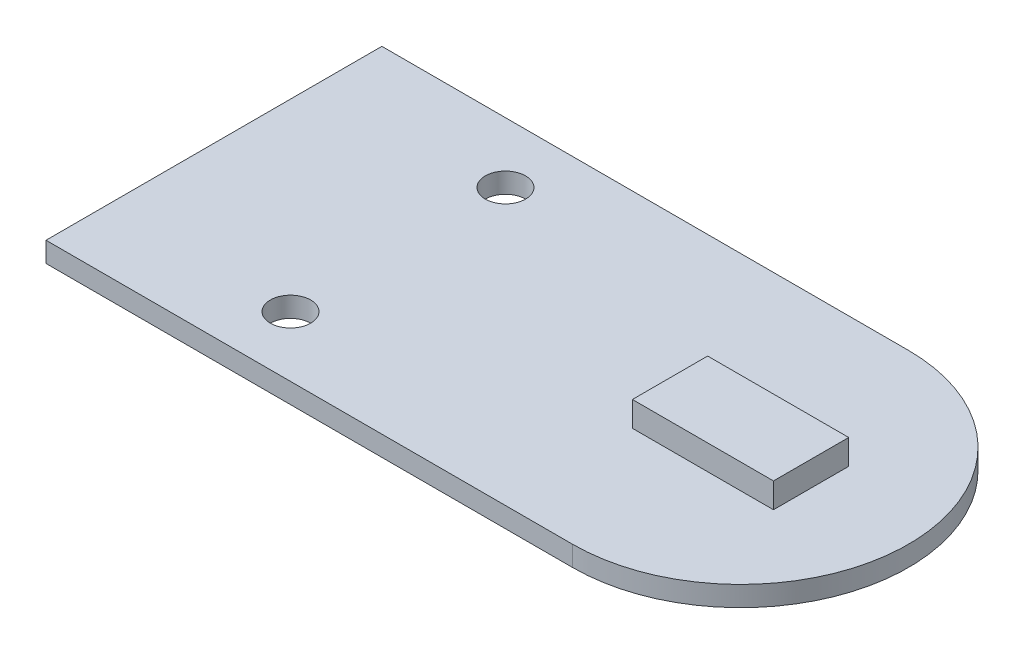
SolidWorks part; units mm, degrees
material "ABS"
ref_plane "Płaszczyzna przednia" through (0, 0, 0) normal (0, 0, 1) x (1, 0, 0)
ref_plane "Płaszczyzna górna" through (0, 0, 0) normal (0, 1, 0) x (1, 0, 0)
ref_plane "Płaszczyzna prawa" through (0, 0, 0) normal (1, 0, 0) x (0, 0, -1)
sketch "Szkic1" plane through (0, 0, 0) normal (0, 1, 0) x (1, 0, 0)
  line L0 (0, -55) -> (0, 55) construction
  line L1 (-39.2, 12.5) -> (0, 12.5)
  line L2 (-39.2, 12.5) -> (-39.2, -12.5)
  line L3 (-39.2, -12.5) -> (0, -12.5)
  line L5 (-55, 0) -> (55, 0) construction
  arc A0 (0, -12.5) -> (0, 12.5) centre (0, 0) ccw
  circle A1 centre (-25.5, 8) radius 1.5
  circle A2 centre (-25.5, -8) radius 1.5
  dimension "D3" = 3
  dimension "D4" = 25.5
  dimension "D5" = 8
  dimension "D1" = 25
  dimension "D2" = 39.2
extrude "Dodanie-wyciągnięcie1" add sketch "Szkic1" along normal blind 1.5
sketch "Szkic2" plane through (0, 1.5, 0) normal (0, 1, 0) x (1, 0, 0)
  line L1 (-5.25, 2.8) -> (5.25, 2.8)
  line L2 (-5.25, 2.8) -> (-5.25, -2.8)
  line L3 (-5.25, -2.8) -> (5.25, -2.8)
  line L4 (5.25, 2.8) -> (5.25, -2.8)
  line L5 (-5.25, 2.8) -> (5.25, -2.8) construction
  line L6 (-5.25, -2.8) -> (5.25, 2.8) construction
  point P0 (0, 0)
  dimension "D1" = 10.5
  dimension "D2" = 5.6
extrude "Dodanie-wyciągnięcie2" add sketch "Szkic2" along normal blind 1.86
